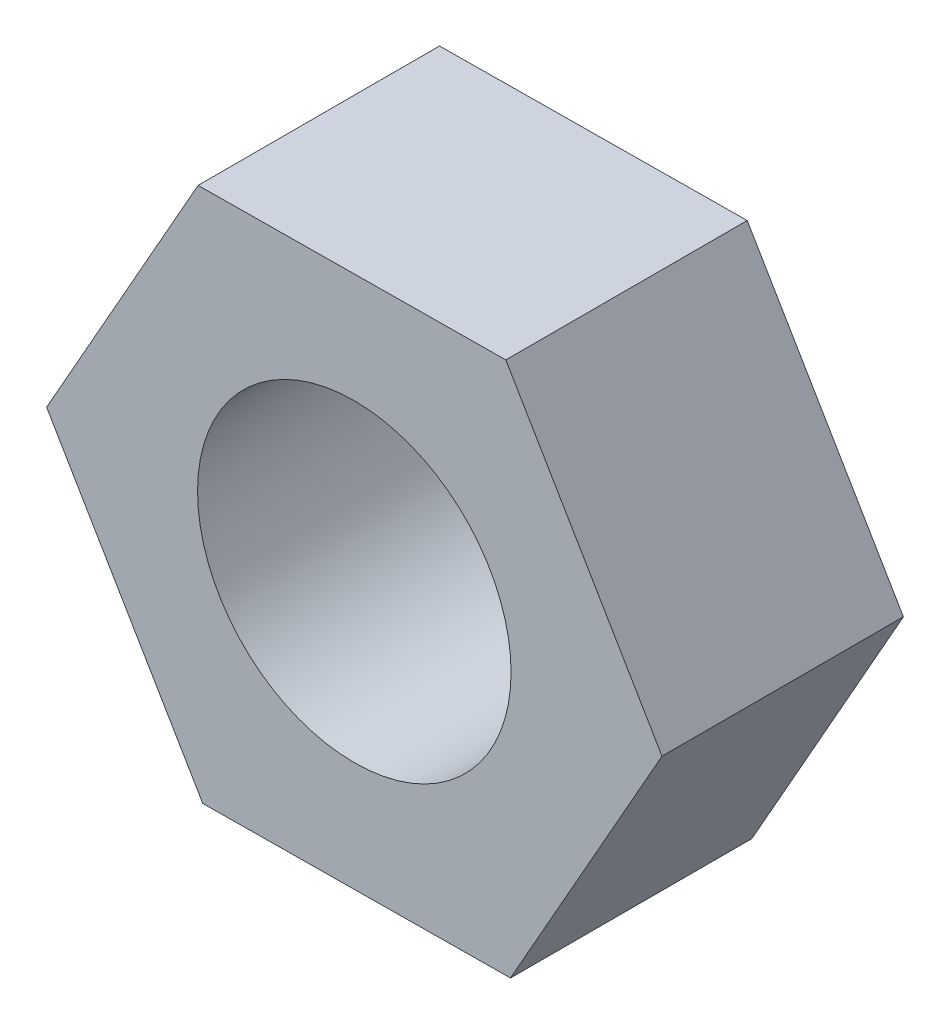
SolidWorks part; units mm, degrees
ref_plane "前视基准面" through (0, 0, 0) normal (0, 0, 1) x (1, 0, 0)
ref_plane "上视基准面" through (0, 0, 0) normal (0, 1, 0) x (1, 0, 0)
ref_plane "右视基准面" through (0, 0, 0) normal (1, 0, 0) x (0, 0, -1)
sketch "草图1" plane through (0, 0, 0) normal (0, 0, 1) x (1, 0, 0)
  line L1 (4.9821, -8.4565) -> (9.8146, 0.0864)
  line L2 (9.8146, 0.0864) -> (4.8325, 8.5429)
  line L3 (4.8325, 8.5429) -> (-4.9821, 8.4565)
  line L4 (-4.9821, 8.4565) -> (-9.8146, -0.0864)
  line L5 (-9.8146, -0.0864) -> (-4.8325, -8.5429)
  line L6 (-4.8325, -8.5429) -> (4.9821, -8.4565)
  circle A0 centre (0, 0) radius 8.5 construction
  circle A1 centre (0, 0) radius 5
  dimension "D1" = 10
  dimension "D2" = 17
extrude "凸台-拉伸1" add sketch "草图1" along normal blind 7.7
